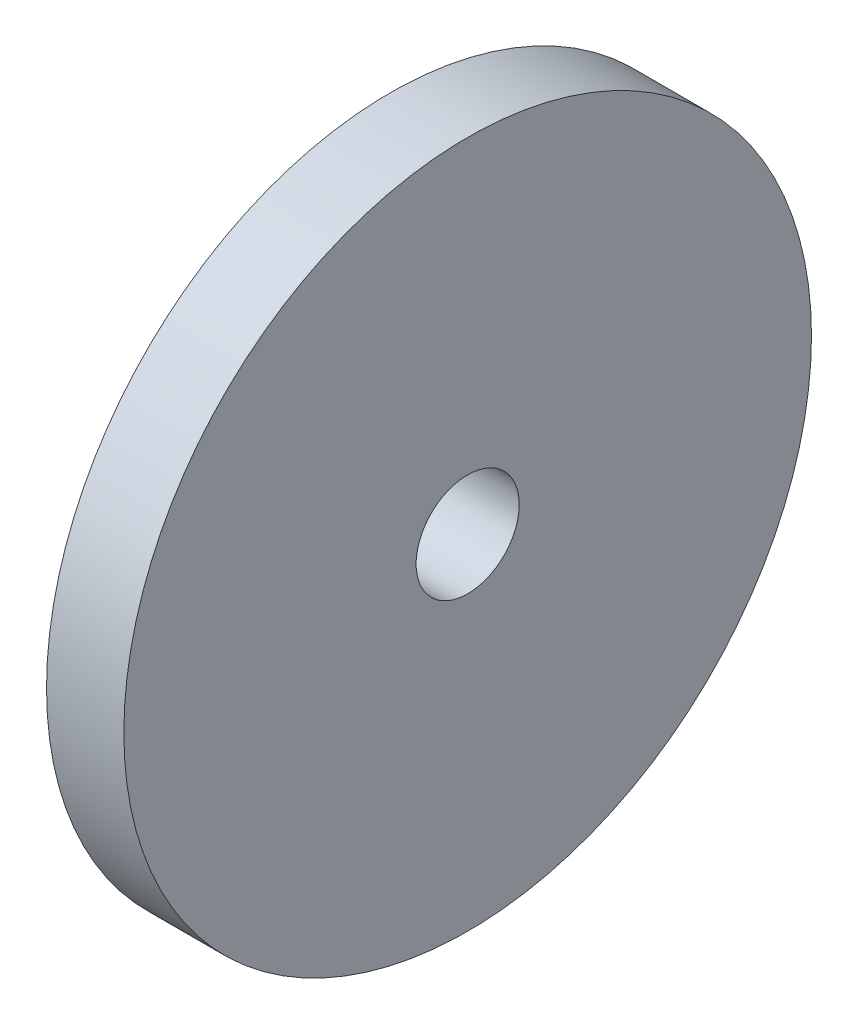
SolidWorks part; units mm, degrees
ref_plane "Front Plane" through (0, 0, 0) normal (0, 0, 1) x (1, 0, 0)
ref_plane "Top Plane" through (0, 0, 0) normal (0, 1, 0) x (1, 0, 0)
ref_plane "Right Plane" through (0, 0, 0) normal (1, 0, 0) x (0, 0, -1)
sketch "Sketch1" plane through (0, 0, 0) normal (1, 0, 0) x (0, 0, -1)
  circle A0 centre (0, 0) radius 33.35
  circle A1 centre (0, 0) radius 5
  dimension "D1" = 66.7
  dimension "D2" = 10
extrude "Boss-Extrude1" add sketch "Sketch1" along normal blind 7.5
